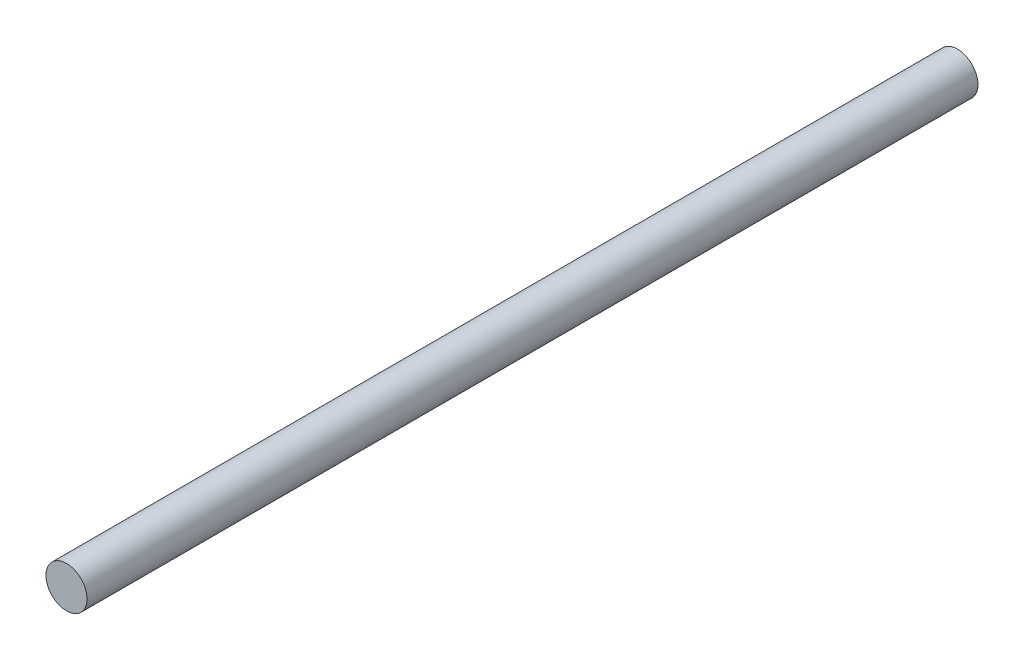
SolidWorks part; units mm, degrees
ref_plane "Front Plane" through (0, 0, 0) normal (0, 0, 1) x (1, 0, 0)
ref_plane "Top Plane" through (0, 0, 0) normal (0, 1, 0) x (1, 0, 0)
ref_plane "Right Plane" through (0, 0, 0) normal (1, 0, 0) x (0, 0, -1)
sketch "Sketch1" plane through (0, 0, 0) normal (0, 0, 1) x (1, 0, 0)
  circle A0 centre (0, 0) radius 1.5
  dimension "D1" = 3
extrude "Boss-Extrude1" add sketch "Sketch1" along normal blind 65
